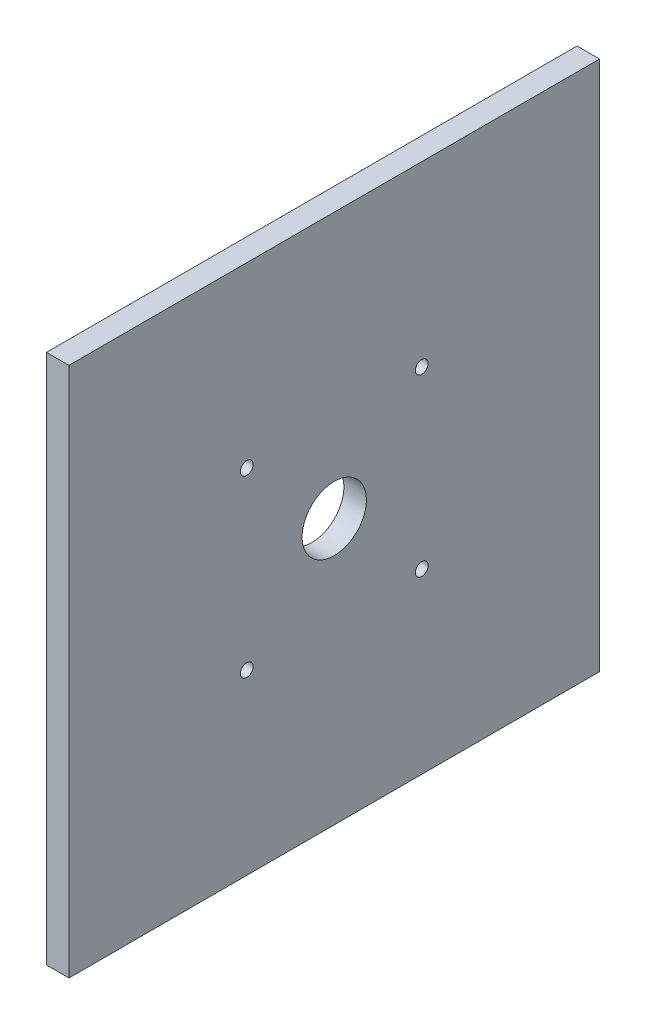
SolidWorks part; units mm, degrees
material "Glass"
ref_plane "Front Plane" through (0, 0, 0) normal (0, 0, 1) x (1, 0, 0)
ref_plane "Top Plane" through (0, 0, 0) normal (0, 1, 0) x (1, 0, 0)
ref_plane "Right Plane" through (0, 0, 0) normal (1, 0, 0) x (0, 0, -1)
sketch "Sketch1" plane through (0, 0, 0) normal (1, 0, 0) x (0, 0, -1)
  line L1 (-16.5, -16.5) -> (16.5, -16.5)
  line L2 (-16.5, -16.5) -> (-16.5, 16.5)
  line L3 (-16.5, 16.5) -> (16.5, 16.5)
  line L4 (16.5, -16.5) -> (16.5, 16.5)
  line L5 (-16.5, -16.5) -> (16.5, 16.5) construction
  line L6 (-16.5, 16.5) -> (16.5, -16.5) construction
  circle A0 centre (0, 0) radius 2
  circle A1 centre (5.4415, -5.4415) radius 0.4
  circle A2 centre (5.4415, -5.4415) radius 0.4 construction
  circle A3 centre (-5.4415, -5.4415) radius 0.4
  circle A4 centre (-5.4415, 5.4415) radius 0.4
  circle A5 centre (5.4415, 5.4415) radius 0.4
  point P0 (0, 0)
  point P21 (0, 0)
  dimension "D2" = 4
  dimension "D1" = 33
  dimension "D3" = 4
extrude "Boss-Extrude1" add sketch "Sketch1" along normal blind 1.4
